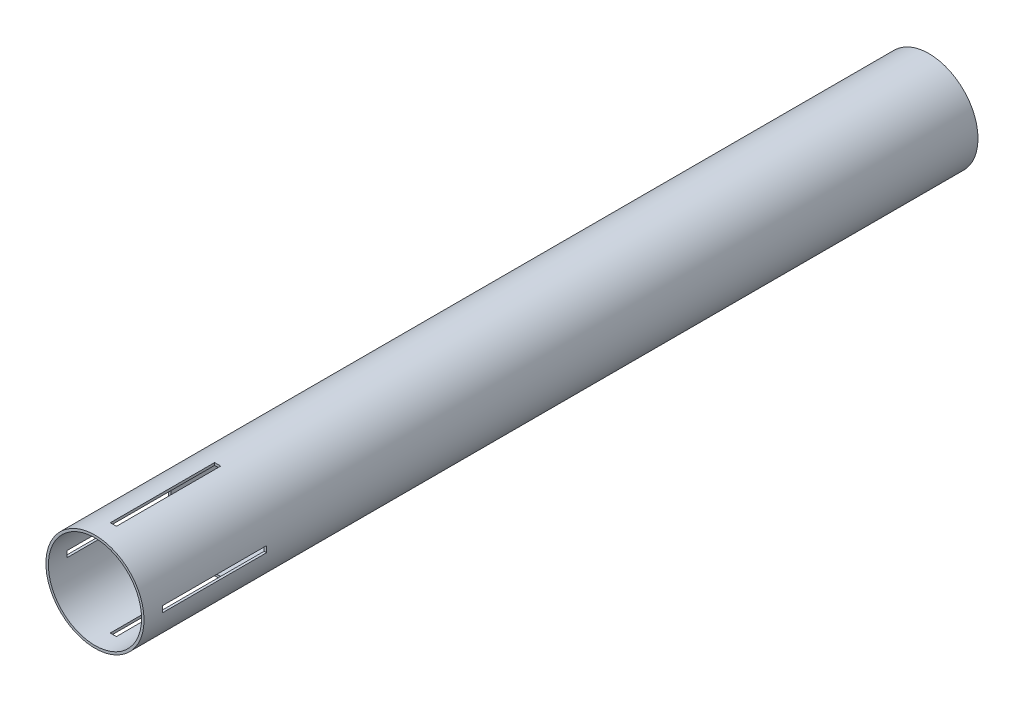
SolidWorks part; units mm, degrees
other "Markup1"
sketch "Sketch5" plane through (50.8, 50.8, 0) normal (0.1901, 0.9762, -0.1044) x (0.0697, 0.0927, 0.9933)
ref_plane "Front Plane" through (0, 0, 0) normal (0, 0, 1) x (1, 0, 0)
ref_plane "Top Plane" through (0, 0, 0) normal (0, 1, 0) x (1, 0, 0)
ref_plane "Right Plane" through (0, 0, 0) normal (1, 0, 0) x (0, 0, -1)
sketch "Sketch1" plane through (0, 0, 0) normal (0, 0, 1) x (1, 0, 0)
  circle A0 centre (0, 0) radius 50.8
  circle A1 centre (0, 0) radius 48.26
  dimension "D1" = 101.6
  dimension "D2" = 2.54
extrude "Boss-Extrude1" add sketch "Sketch1" along normal blind 863.6
sketch "Sketch2" plane through (0, 0, 863.6) normal (0, 0, 1) x (1, 0, 0)
  line L2 (-3.175, 50.7007) -> (-3.175, 48.1554)
  line L4 (3.175, 50.7007) -> (3.175, 48.1554)
  line L5 (-50.7007, 3.175) -> (-48.1554, 3.175)
  line L7 (-50.7007, -3.175) -> (-48.1554, -3.175)
  line L12 (48.1554, 3.175) -> (50.7007, 3.175)
  line L13 (48.1554, -3.175) -> (50.7007, -3.175)
  line L14 (3.175, -48.1554) -> (3.175, -50.7007)
  line L15 (-3.175, -48.1554) -> (-3.175, -50.7007)
  circle A0 centre (0, 0) radius 50.8 construction
  circle A1 centre (0, 0) radius 48.26 construction
  arc A2 (3.175, 50.7007) -> (-3.175, 50.7007) centre (0, 0) ccw
  arc A3 (3.175, 48.1554) -> (-3.175, 48.1554) centre (0, 0) ccw
  arc A4 (-48.1554, 3.175) -> (-48.1554, -3.175) centre (0, 0) ccw
  arc A5 (-50.7007, 3.175) -> (-50.7007, -3.175) centre (0, 0) ccw
  arc A6 (-3.175, -50.7007) -> (3.175, -50.7007) centre (0, 0) ccw
  arc A7 (-3.175, -48.1554) -> (3.175, -48.1554) centre (0, 0) ccw
  arc A8 (50.7007, -3.175) -> (50.7007, 3.175) centre (0, 0) ccw
  arc A9 (48.1554, -3.175) -> (48.1554, 3.175) centre (0, 0) ccw
  dimension "D1" = 6.35
extrude "Cut-Extrude1" cut sketch "Sketch2" against normal blind 127
sketch "Sketch4" plane through (0, 0, 863.6) normal (0, 0, 1) x (1, 0, 0)
  line L0 (50.7007, 3.175) -> (48.1554, 3.175) construction
  line L1 (48.1554, -3.175) -> (50.7007, -3.175) construction
  line L2 (-3.175, 50.7007) -> (-3.175, 48.1554)
  line L3 (3.175, 48.1554) -> (3.175, 50.7007)
  line L4 (-3.175, 50.7007) -> (-3.175, 48.1554)
  line L5 (3.175, 48.1554) -> (3.175, 50.7007)
  line L6 (3.175, -50.7007) -> (3.175, -48.1554) construction
  line L7 (-3.175, -48.1554) -> (-3.175, -50.7007) construction
  line L8 (-48.1554, 3.175) -> (-50.7007, 3.175) construction
  line L9 (-50.7007, -3.175) -> (-48.1554, -3.175) construction
  line L10 (50.7007, 3.175) -> (48.1554, 3.175)
  line L11 (48.1554, -3.175) -> (50.7007, -3.175)
  line L12 (3.175, -50.7007) -> (3.175, -48.1554)
  line L13 (-3.175, -48.1554) -> (-3.175, -50.7007)
  line L14 (-48.1554, 3.175) -> (-50.7007, 3.175)
  line L15 (-50.7007, -3.175) -> (-48.1554, -3.175)
  arc A0 (50.7007, -3.175) -> (50.7007, 3.175) centre (0, 0) ccw construction
  arc A1 (48.1554, -3.175) -> (48.1554, 3.175) centre (0, 0) ccw construction
  arc A2 (3.175, 50.7007) -> (-3.175, 50.7007) centre (0, 0) ccw
  arc A3 (3.175, 48.1554) -> (-3.175, 48.1554) centre (0, 0) ccw
  arc A4 (3.175, 50.7007) -> (-3.175, 50.7007) centre (0, 0) ccw
  arc A5 (3.175, 48.1554) -> (-3.175, 48.1554) centre (0, 0) ccw
  arc A6 (-3.175, -50.7007) -> (3.175, -50.7007) centre (0, 0) ccw construction
  arc A7 (-3.175, -48.1554) -> (3.175, -48.1554) centre (0, 0) ccw construction
  arc A8 (-48.1554, 3.175) -> (-48.1554, -3.175) centre (0, 0) ccw construction
  arc A9 (-50.7007, 3.175) -> (-50.7007, -3.175) centre (0, 0) ccw construction
  arc A10 (50.7007, -3.175) -> (50.7007, 3.175) centre (0, 0) ccw
  arc A11 (48.1554, -3.175) -> (48.1554, 3.175) centre (0, 0) ccw
  arc A12 (-3.175, -50.7007) -> (3.175, -50.7007) centre (0, 0) ccw
  arc A13 (-3.175, -48.1554) -> (3.175, -48.1554) centre (0, 0) ccw
  arc A14 (-48.1554, 3.175) -> (-48.1554, -3.175) centre (0, 0) ccw
  arc A15 (-50.7007, 3.175) -> (-50.7007, -3.175) centre (0, 0) ccw
  dimension "D1" = 0
extrude "Boss-Extrude2" add sketch "Sketch4" against normal blind 19.05
